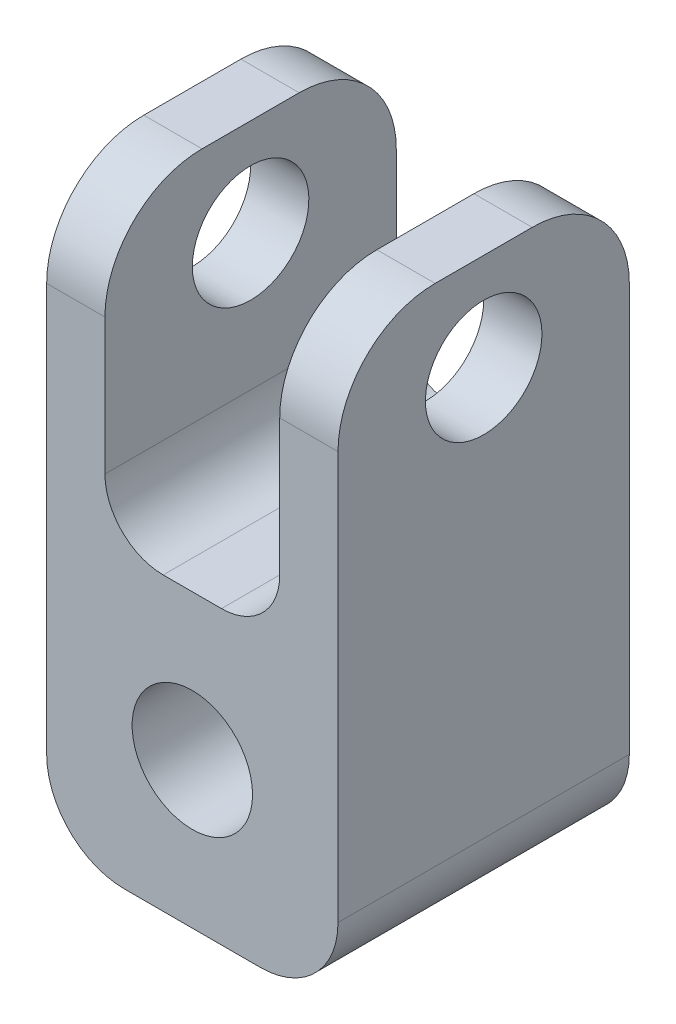
SolidWorks part; units mm, degrees
ref_plane "Front Plane" through (0, 0, 0) normal (0, 0, 1) x (1, 0, 0)
ref_plane "Top Plane" through (0, 0, 0) normal (0, 1, 0) x (1, 0, 0)
ref_plane "Right Plane" through (0, 0, 0) normal (1, 0, 0) x (0, 0, -1)
sketch "Sketch2" plane through (0, 0, 0) normal (0, 0, 1) x (1, 0, 0)
  line L1 (-15, 15) -> (15, 15)
  line L2 (-15, 15) -> (-15, -15)
  line L3 (-15, -15) -> (15, -15)
  line L4 (15, 15) -> (15, -15)
  line L5 (-15, 15) -> (15, -15) construction
  line L6 (-15, -15) -> (15, 15) construction
  circle A0 centre (0, 0) radius 6.2
  point P0 (0, 0)
  dimension "D3" = 12.4
  dimension "D1" = 30
  dimension "D2" = 30
extrude "Boss-Extrude2" add sketch "Sketch2" along normal blind 30
sketch "Sketch4" plane through (0, 15, 0) normal (0, 1, 0) x (1, 0, 0)
  line L0 (-15, -30) -> (-9, -30)
  line L1 (15, -30) -> (-15, -30) construction
  line L2 (-9, -30) -> (-9, 0)
  line L3 (15, 0) -> (-15, 0) construction
  line L4 (-9, 0) -> (-15, 0)
  line L5 (-15, 0) -> (-15, -30)
  line L6 (9, -30) -> (15, -30)
  line L7 (15, -30) -> (15, 0)
  line L8 (15, 0) -> (9, 0)
  line L9 (9, 0) -> (9, -30)
  dimension "D1" = 6
  dimension "D2" = 6
extrude "Boss-Extrude3" add sketch "Sketch4" along normal blind 30
fillet "Fillet1" radius 8 2 edges at (15, -15, 15) (-15, -15, 15)
fillet "Fillet4" radius 10 4 edges at (12, 45, 30) (12, 45, 0) (-12, 45, 0) (-12, 45, 30)
sketch "Sketch5" plane through (-15, 0, 0) normal (-1, 0, 0) x (0, 0, 1)
  circle A0 centre (15, 35) radius 6
  point P2 (0, 0)
  dimension "D1" = 12
extrude "Cut-Extrude1" cut sketch "Sketch5" against normal blind 30
fillet "Fillet5" radius 6 2 edges at (9, 15, 15) (-9, 15, 15)
